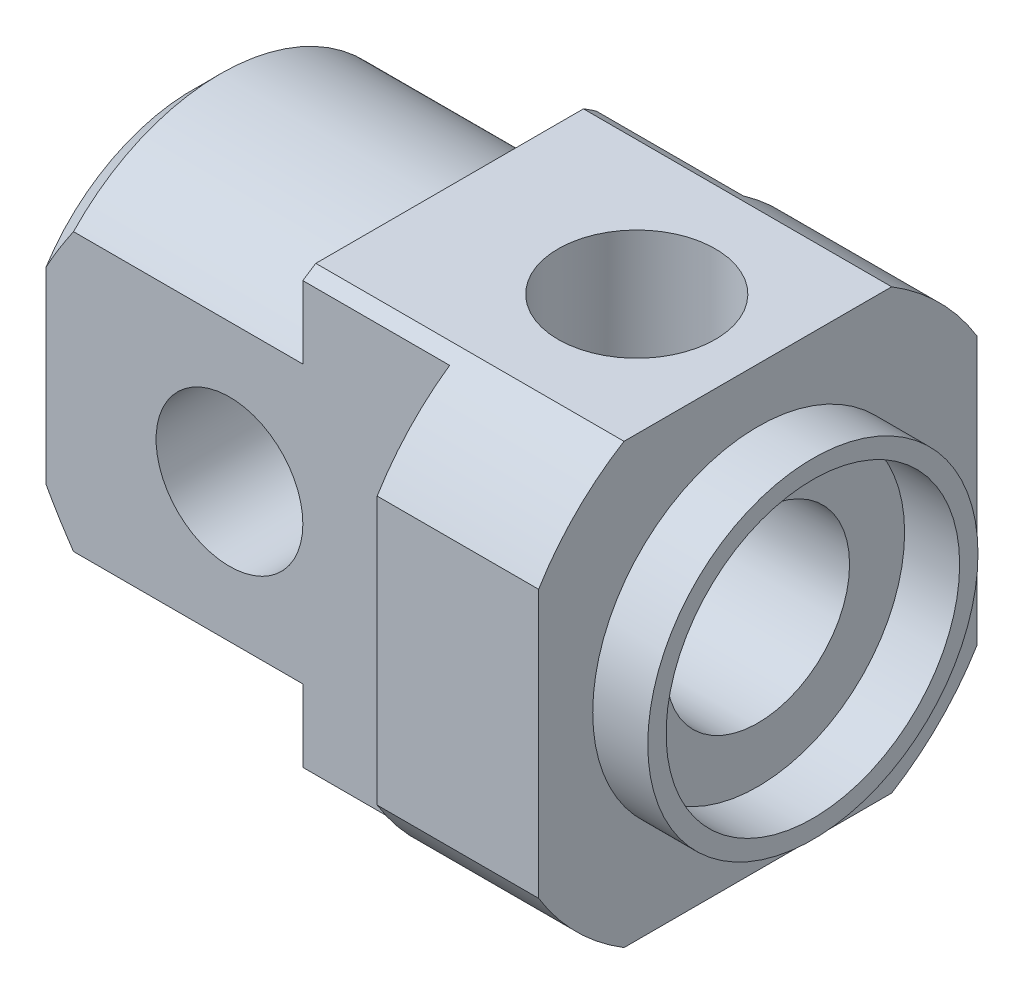
SolidWorks part; units mm, degrees
ref_plane "Alzado" through (0, 0, 0) normal (0, 0, 1) x (1, 0, 0)
ref_plane "Planta" through (0, 0, 0) normal (0, 1, 0) x (1, 0, 0)
ref_plane "Vista lateral" through (0, 0, 0) normal (1, 0, 0) x (0, 0, -1)
sketch "Croquis1" plane through (0, 0, 0) normal (0, 1, 0) x (1, 0, 0)
  line L0 (0, 0) -> (30.8, 0)
  line L1 (30.8, 0) -> (30.8, 14)
  line L2 (30.8, 14) -> (14, 14)
  line L3 (14, 14) -> (14, 11)
  line L4 (14, 11) -> (1.5, 11)
  line L5 (1.5, 11) -> (0, 9.5)
  line L6 (0, 9.5) -> (0, 0)
  dimension "D1" = 30.8
  dimension "D2" = 14
  dimension "D3" = 9.5
  dimension "D4" = 16.8
  dimension "D5" = 3
  dimension "D6" = 12.5
revolve "Revolución1" add sketch "Croquis1" angle 360 about L0
sketch "Croquis2" plane through (0, 0, 0) normal (1, 0, 0) x (0, 0, -1)
  line L1 (-11.95, -11.95) -> (11.95, -11.95)
  line L2 (-11.95, -11.95) -> (-11.95, 11.95)
  line L3 (-11.95, 11.95) -> (11.95, 11.95)
  line L4 (11.95, -11.95) -> (11.95, 11.95)
  line L5 (-11.95, -11.95) -> (11.95, 11.95) construction
  line L6 (-11.95, 11.95) -> (11.95, -11.95) construction
  point P0 (0, 0)
  dimension "D1" = 23.9
extrude "Cortar-Extruir1" cut sketch "Croquis2" along normal through all flip side to cut
sketch "Croquis3" plane through (0, 0, 0) normal (1, 0, 0) x (0, 0, -1)
  line L1 (-8, -16) -> (8, -16)
  line L2 (-8, -16) -> (-8, 16)
  line L3 (-8, 16) -> (8, 16)
  line L4 (8, -16) -> (8, 16)
  line L5 (-8, -16) -> (8, 16) construction
  line L6 (-8, 16) -> (8, -16) construction
  point P0 (0, 0)
  dimension "D1" = 16
  dimension "D2" = 32
extrude "Cortar-Extruir2" cut sketch "Croquis3" along normal blind 22 flip side to cut
sketch "Croquis4" plane through (30.8, 0, 0) normal (1, 0, 0) x (0, 0, -1)
  circle A0 centre (0, 0) radius 9
  circle A1 centre (0, 0) radius 8
  dimension "D1" = 18
  dimension "D2" = 16
extrude "Saliente-Extruir1" add sketch "Croquis4" along normal blind 3
sketch "Croquis5" plane through (0, 0, 8) normal (0, 0, 1) x (1, 0, 0)
  line L0 (1.5, 7.5498) -> (14, 7.5498) construction
  line L1 (0, 5.1235) -> (0, -5.1235) construction
  circle A0 centre (10, 0) radius 4
  dimension "D1" = 7.5498
  dimension "D2" = 10
  dimension "D3" = 8
extrude "Cortar-Extruir3" cut sketch "Croquis5" against normal through all
sketch "Croquis7" plane through (0, 11.95, 0) normal (0, 1, 0) x (1, 0, 0)
  line L0 (30.8, -9) -> (30.8, 9) construction
  circle A0 centre (24.2, 0) radius 4.283
  dimension "D1" = 6.6
  dimension "D2" = 8.566
sketch "Croquis8" plane through (30.8, 0, 0) normal (1, 0, 0) x (0, 0, -1)
  circle A0 centre (0, 0) radius 5
  dimension "D1" = 10
extrude "Cortar-Extruir4" cut sketch "Croquis8" against normal blind 13 contours A0
extrude "Cortar-Extruir5" cut sketch "Croquis7" against normal blind 13 contours A0
